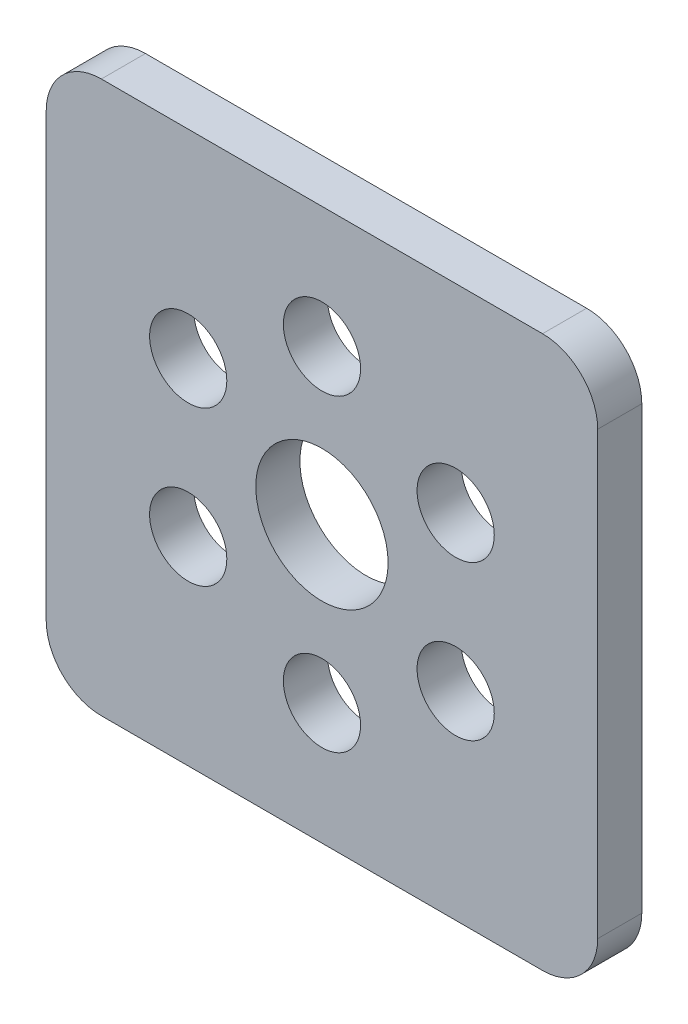
SolidWorks part; units mm, degrees
material "ABS"
ref_plane "前视基准面" through (0, 0, 0) normal (0, 0, 1) x (1, 0, 0)
ref_plane "上视基准面" through (0, 0, 0) normal (0, 1, 0) x (1, 0, 0)
ref_plane "右视基准面" through (0, 0, 0) normal (1, 0, 0) x (0, 0, -1)
sketch "草图1" plane through (0, 0, 0) normal (0, 0, 1) x (1, 0, 0)
  line L1 (25, 25) -> (-25, 25)
  line L2 (25, 25) -> (25, -25)
  line L3 (25, -25) -> (-25, -25)
  line L4 (-25, 25) -> (-25, -25)
  line L5 (0, -25) -> (0, 25) construction
  line L6 (25, 0) -> (-25, 0) construction
  circle A0 centre (0, 0) radius 14 construction
  circle A1 centre (0, 14) radius 3.5
  circle A2 centre (12.1244, 7) radius 3.5
  circle A3 centre (12.1244, -7) radius 3.5
  circle A4 centre (0, -14) radius 3.5
  circle A5 centre (-12.1244, -7) radius 3.5
  circle A6 centre (-12.1244, 7) radius 3.5
  circle A7 centre (0, 0) radius 6
  point P0 (0, 0)
  point P21 (0, 0)
  dimension "D3" = 28
  dimension "D4" = 7
  dimension "D6" = 12
  dimension "D1" = 50
  dimension "D2" = 50
  dimension "D5" = 6
extrude "凸台-拉伸1" add sketch "草图1" along normal blind 4
fillet "圆角1" radius 5 4 edges at (25, -25, 2) (-25, -25, 2) (-25, 25, 2) (25, 25, 2)
